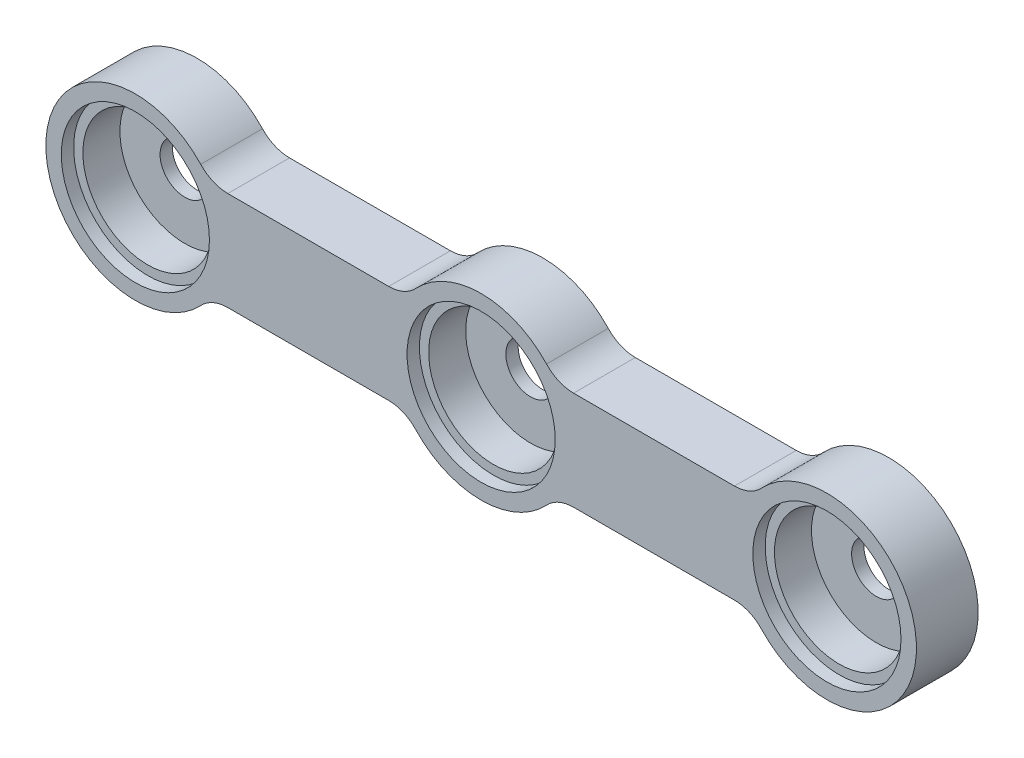
SolidWorks part; units mm, degrees
ref_plane "Front Plane" through (0, 0, 0) normal (0, 0, 1) x (1, 0, 0)
ref_plane "Top Plane" through (0, 0, 0) normal (0, 1, 0) x (1, 0, 0)
ref_plane "Right Plane" through (0, 0, 0) normal (1, 0, 0) x (0, 0, -1)
sketch "Sketch1" plane through (0, 0, 0) normal (0, 0, 1) x (1, 0, 0)
  line L0 (-68.7583, 0) -> (-12.7483, 0) construction
  line L1 (-68.7583, 4) -> (-12.7483, 4)
  line L2 (-68.7583, -4) -> (-12.7483, -4)
  line L3 (-40.7533, 24.4745) -> (-40.7533, -26.4527) construction
  arc A0 (-68.7583, 4) -> (-68.7583, -4) centre (-68.7583, 0) ccw
  arc A1 (-12.7483, -4) -> (-12.7483, 4) centre (-12.7483, 0) ccw
  point P3 (-40.7533, 0)
  dimension "D1" = 56.01
  dimension "D4" = 8
extrude "Boss-Extrude1" add sketch "Sketch1" along normal blind 5
sketch "Sketch2" plane through (0, 0, 0) normal (0, 0, -1) x (-1, 0, 0)
  line L0 (40.7533, 21.3559) -> (40.7533, -25.0317) construction
  line L1 (-42.2604, 0) -> (84.0743, 0) construction
  line L2 (68.7583, 4) -> (68.7583, -11.3535) construction
  line L3 (12.7483, 4) -> (12.7483, -11.3535) construction
  circle A3 centre (40.7533, 0) radius 7.25
  circle A4 centre (68.7583, 0) radius 7.25
  circle A5 centre (12.7483, 0) radius 7.25
  dimension "D1" = 28.005
extrude "Boss-Extrude2" add sketch "Sketch2" against normal blind 5
sketch "Sketch5" plane through (0, 0, 5) normal (0, 0, 1) x (1, 0, 0)
  circle A0 centre (-68.7583, 0) radius 6
  circle A1 centre (-40.7533, 0) radius 6
  circle A2 centre (-12.7483, 0) radius 6
extrude "Cut-Extrude2" cut sketch "Sketch5" against normal blind 1 contours A0 | A1 | A2
sketch "Sketch6" plane through (0, 0, 0) normal (0, 0, -1) x (-1, 0, 0)
  line L0 (-42.0515, 0) -> (123.5582, 0) construction
  line L1 (40.7533, 32.5519) -> (40.7533, -29.3799) construction
  line L2 (12.7483, 15.7982) -> (12.7483, -20.3137) construction
  line L3 (68.7583, 15.7982) -> (68.7583, -20.3137) construction
  circle A0 centre (12.7483, 0) radius 2
  circle A1 centre (40.7533, 0) radius 2
  circle A2 centre (68.7583, 0) radius 2
  dimension "D1" = 28.005
  dimension "D2" = 0
extrude "Cut-Extrude3" cut sketch "Sketch6" against normal blind 4
fillet "Fillet1" radius 3 8 edges at (-18.795, 4, 2.5) (-18.795, -4, 2.5) (-34.7066, -4, 2.5) (-46.8, -4, 2.5) (-46.8, 4, 2.5) (-34.7066, 4, 2.5) (-62.7116, -4, 2.5) (-62.7116, 4, 2.5)
sketch "Sketch7" plane through (0, 0, 4) normal (0, 0, 1) x (1, 0, 0)
  circle A0 centre (-68.7583, 0) radius 5.25
  circle A1 centre (-40.7533, 0) radius 5.25
  circle A2 centre (-12.7483, 0) radius 5.25
extrude "Cut-Extrude4" cut sketch "Sketch7" against normal blind 3
